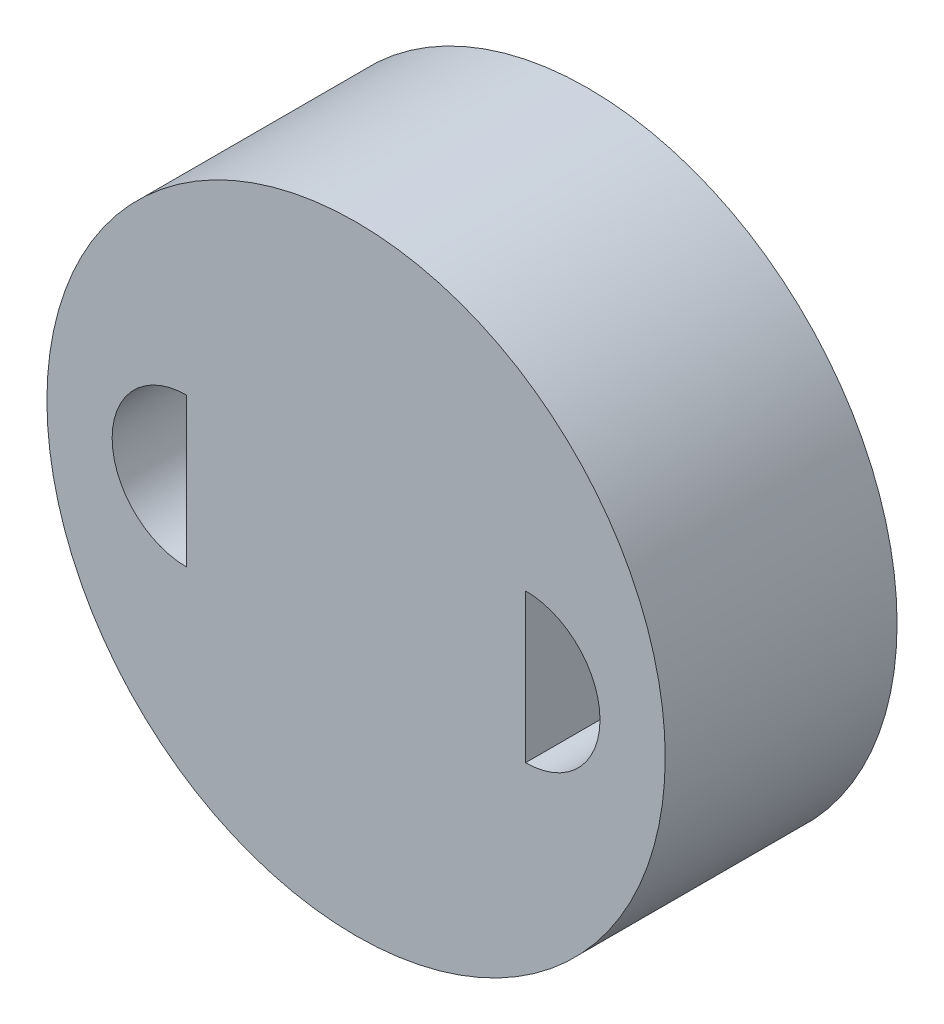
SolidWorks part; units mm, degrees
material "ABS"
ref_plane "Front Plane" through (0, 0, 0) normal (0, 0, 1) x (1, 0, 0)
ref_plane "Top Plane" through (0, 0, 0) normal (0, 1, 0) x (1, 0, 0)
ref_plane "Right Plane" through (0, 0, 0) normal (1, 0, 0) x (0, 0, -1)
sketch "Sketch1" plane through (0, 0, 0) normal (0, 0, 1) x (1, 0, 0)
  circle A0 centre (0, 0) radius 101.6
  point P23 (0, 0)
  dimension "D1" = 203.2
extrude "Boss-Extrude1" add sketch "Sketch1" along normal blind 76.2 contours A0
sketch "Sketch2" plane through (0, 0, 76.2) normal (0, 0, 1) x (1, 0, 0)
  line L8 (-55.703, 24.4622) -> (55.703, 24.4622)
  line L9 (-55.703, 24.4622) -> (-55.703, -24.4622)
  line L10 (-55.703, -24.4622) -> (55.703, -24.4622)
  line L11 (55.703, 24.4622) -> (55.703, -24.4622)
  line L12 (-55.703, 24.4622) -> (55.703, -24.4622) construction
  line L13 (-55.703, -24.4622) -> (55.703, 24.4622) construction
  arc A1 (55.703, -24.4622) -> (55.703, 24.4622) centre (55.703, 0) ccw
  arc A2 (-55.703, -24.4622) -> (-55.703, 24.4622) centre (-55.703, 0) cw
  point P0 (0, 0)
  point P14 (0, 0)
extrude "Cut-Extrude7" cut sketch "Sketch2" against normal through all both and the other way through all contours A2 L9 | L11 A1
